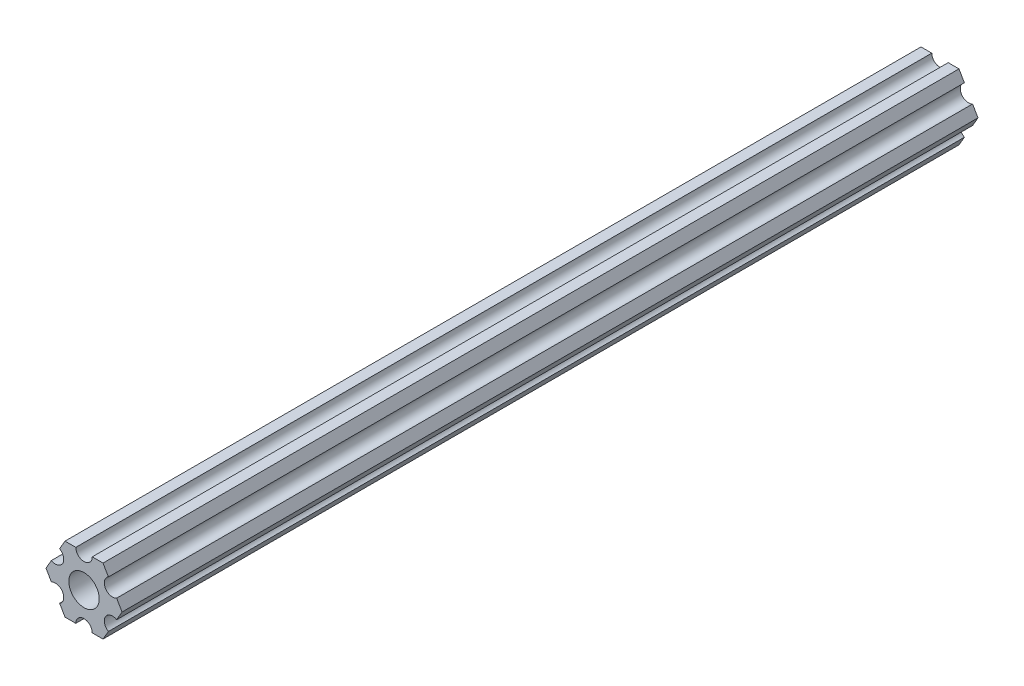
SolidWorks part; units mm, degrees
ref_plane "Front Plane" through (0, 0, 0) normal (0, 0, 1) x (1, 0, 0)
ref_plane "Top Plane" through (0, 0, 0) normal (0, 1, 0) x (1, 0, 0)
ref_plane "Right Plane" through (0, 0, 0) normal (1, 0, 0) x (0, 0, -1)
ref_plane "Plane1" through (0, 0, 0) normal (0, 0, -1) x (-1, 0, 0)
sketch "Sketch1" plane through (0, 0, 0) normal (0, 0, -1) x (-1, 0, 0)
  line L0 (-4.7055, -4.5498) -> (-3.6662, -6.35)
  line L1 (-3.6662, -6.35) -> (-1.5875, -6.35)
  line L2 (1.5875, -6.35) -> (3.6662, -6.35)
  line L3 (3.6662, -6.35) -> (4.7055, -4.5498)
  line L4 (6.293, -1.8002) -> (7.3323, 0)
  line L5 (7.3323, 0) -> (6.293, 1.8002)
  line L6 (4.7055, 4.5498) -> (3.6662, 6.35)
  line L7 (3.6662, 6.35) -> (1.5875, 6.35)
  line L8 (-1.5875, 6.35) -> (-3.6662, 6.35)
  line L9 (-3.6662, 6.35) -> (-4.7055, 4.5498)
  line L10 (-6.293, 1.8002) -> (-7.3323, 0)
  line L11 (-7.3323, 0) -> (-6.293, -1.8002)
  circle A0 centre (0, 0) radius 2.9337
  arc A1 (-6.293, -1.8002) -> (-4.7055, -4.5498) centre (-5.4993, -3.175) cw
  arc A2 (-1.5875, -6.35) -> (1.5875, -6.35) centre (0, -6.35) cw
  arc A3 (4.7055, -4.5498) -> (6.293, -1.8002) centre (5.4993, -3.175) cw
  arc A4 (6.293, 1.8002) -> (4.7055, 4.5498) centre (5.4993, 3.175) cw
  arc A5 (1.5875, 6.35) -> (-1.5875, 6.35) centre (0, 6.35) cw
  arc A6 (-4.7055, 4.5498) -> (-6.293, 1.8002) centre (-5.4993, 3.175) cw
extrude "Boss-Extrude1" add sketch "Sketch1" along normal blind 165.1
